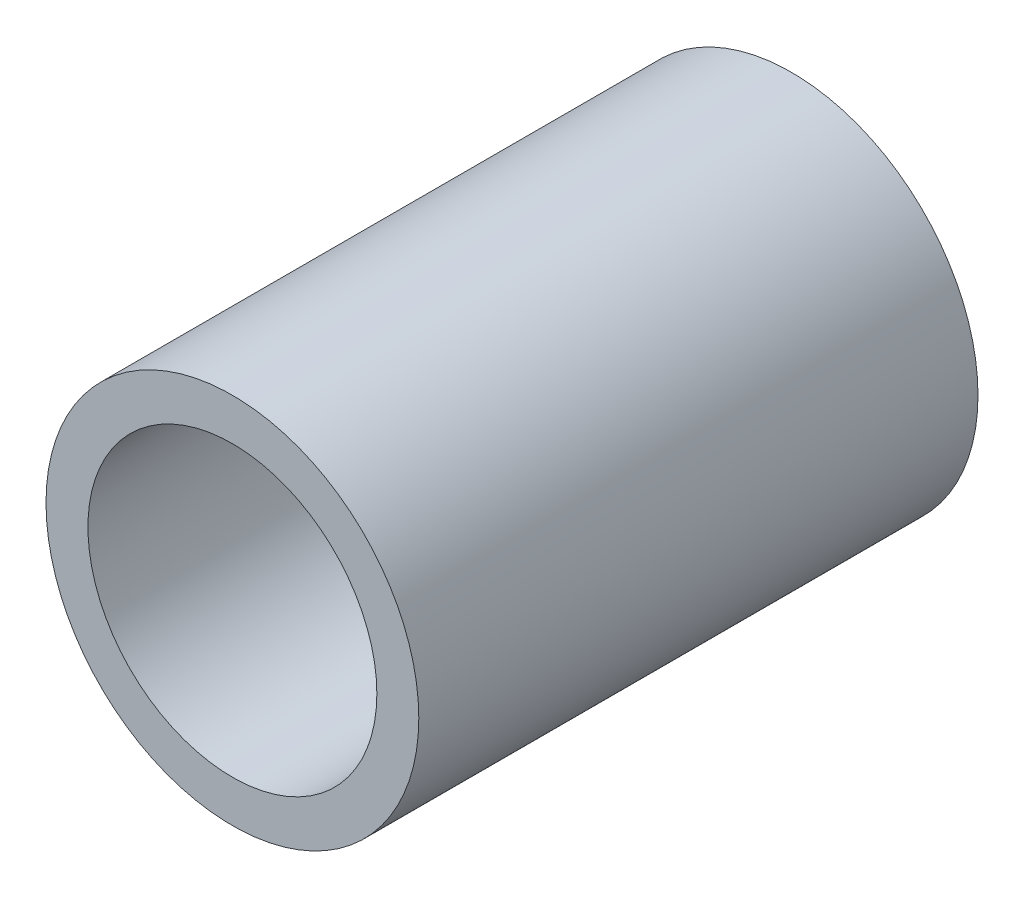
SolidWorks part; units mm, degrees
ref_plane "Спереди" through (0, 0, 0) normal (0, 0, 1) x (1, 0, 0)
ref_plane "Сверху" through (0, 0, 0) normal (0, 1, 0) x (1, 0, 0)
ref_plane "Справа" through (0, 0, 0) normal (1, 0, 0) x (0, 0, -1)
sketch "Эскиз1" plane through (0, 0, 0) normal (0, 0, 1) x (1, 0, 0)
  circle A0 centre (0, 0) radius 1
  circle A1 centre (0, 0) radius 0.775
extrude "Бобышка-Вытянуть1" add sketch "Эскиз1" along normal blind 3
